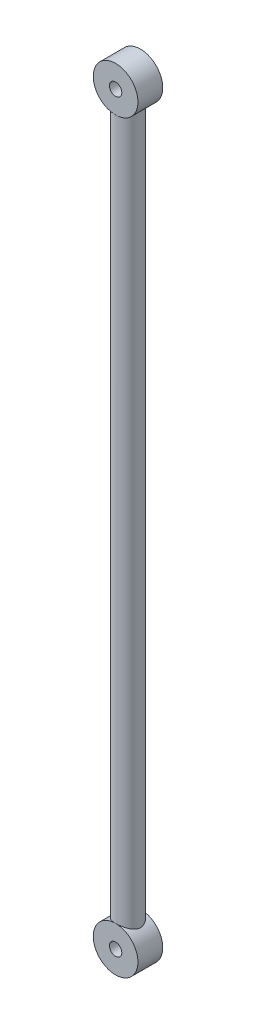
SolidWorks part; units mm, degrees
material "氧化铝"
ref_plane "前视基准面" through (0, 0, 0) normal (0, 0, 1) x (1, 0, 0)
ref_plane "上视基准面" through (0, 0, 0) normal (0, 1, 0) x (1, 0, 0)
ref_plane "右视基准面" through (0, 0, 0) normal (1, 0, 0) x (0, 0, -1)
sketch "草图1" plane through (0, 0, 0) normal (0, 1, 0) x (1, 0, 0)
  circle A0 centre (0, 0) radius 5
  dimension "D1" = 10
extrude "凸台-拉伸1" add sketch "草图1" along normal mid plane 300
sketch "草图2" plane through (0, 0, 0) normal (0, 0, 1) x (1, 0, 0)
  line L0 (5, 150) -> (-5, 150) construction
  line L1 (-5, -150) -> (5, -150) construction
  circle A0 centre (0, 150) radius 9
  circle A1 centre (0, -150) radius 9
  dimension "D1" = 18
  dimension "D2" = 18
extrude "凸台-拉伸2" add sketch "草图2" along normal mid plane 10
sketch "草图3" plane through (0, 0, 5) normal (0, 0, 1) x (1, 0, 0)
  circle A0 centre (0, 150) radius 2.5
  circle A1 centre (0, -150) radius 2.5
  dimension "D1" = 5
  dimension "D2" = 5
extrude "切除-拉伸1" cut sketch "草图3" against normal up to next
